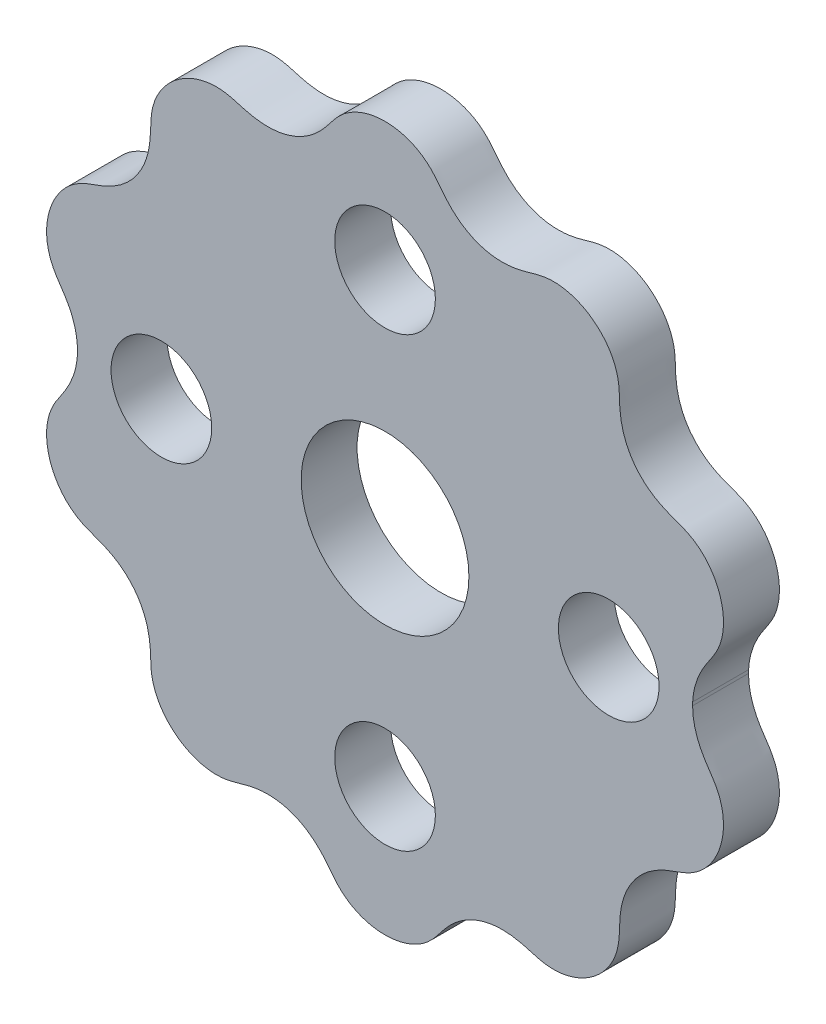
SolidWorks part; units mm, degrees
ref_plane "Front Plane" through (0, 0, 0) normal (0, 0, 1) x (1, 0, 0)
ref_plane "Top Plane" through (0, 0, 0) normal (0, 1, 0) x (1, 0, 0)
ref_plane "Right Plane" through (0, 0, 0) normal (1, 0, 0) x (0, 0, -1)
sketch "Sketch2" plane through (0, 0, 0) normal (0, 0, 1) x (1, 0, 0)
  spline S0 degree 4 poles (25.7736, 13.6742) (25.8686, 13.6396) (26.0587, 13.5707) (26.4395, 13.4348) (27.0042, 13.2114) (27.6294, 12.8737) (28.3868, 12.2959) (29.1238, 11.4849) (29.7675, 10.4058) (30.2051, 9.0603) (30.3194, 7.7572) (30.1819, 6.6864) (29.9333, 5.8919) (29.6914, 5.3551) (29.4615, 4.9441) (29.2046, 4.5499) (28.9379, 4.1623) (28.6806, 3.776) (28.4419, 3.3849) (28.2266, 2.9879) (28.0374, 2.5839) (27.8738, 2.1703) (27.7378, 1.7443) (27.6309, 1.3144) (27.5637, 0.9252) (27.5253, 0.6016) (27.5084, 0.3452) (27.502, 0.1683) (27.4994, 0.0141) (27.5004, -0.1164) (27.5075, -0.34) (27.5238, -0.57) (27.5481, -0.7918) (27.5805, -1.0166) (27.6209, -1.2405) (27.6691, -1.4621) (27.7251, -1.682) (27.7886, -1.9) (27.8772, -2.1695) (27.998, -2.4878) (28.159, -2.8512) (28.3712, -3.2608) (28.6095, -3.6641) (28.8695, -4.0622) (29.143, -4.4598) (29.4106, -4.8616) (29.6529, -5.2796) (29.9094, -5.8265) (30.1722, -6.6328) (30.3203, -7.7183) (30.2089, -9.0614) (29.7491, -10.4641) (29.0339, -11.6246) (28.2481, -12.4251) (27.5333, -12.9239) (26.9793, -13.2134) (26.518, -13.4062) (26.0478, -13.5746) (25.5777, -13.7437) (24.8251, -14.0429) (23.8272, -14.5611) (22.8619, -15.3341) (22.0408, -16.3838) (21.5281, -17.3765) (21.2286, -18.2328) (21.0669, -19.0171) (20.9945, -19.7066) (20.9671, -20.2928) (20.9548, -20.7736) (20.9338, -21.2542) (20.8816, -21.7329) (20.7645, -22.3233) (20.4996, -23.1258) (19.979, -24.0851) (19.0973, -25.1016) (17.8982, -25.9622) (16.6335, -26.4775) (15.3979, -26.6788) (14.3959, -26.6234) (13.6603, -26.4593) (12.9394, -26.2468) (12.0379, -25.9873) (10.7995, -25.7763) (9.4348, -25.8506) (8.155, -26.2277) (7.1615, -26.7369) (6.4222, -27.2569) (5.7489, -27.8783) (5.2229, -28.4924) (4.8001, -29.0515) (4.4288, -29.5161) (4.1076, -29.8677) (3.6695, -30.271) (2.9854, -30.7618) (1.9994, -31.2314) (0.6852, -31.5347) (-0.7982, -31.5227) (-2.1286, -31.1899) (-3.1354, -30.6771) (-3.8296, -30.1398) (-4.2741, -29.694) (-4.5985, -29.309) (-4.9048, -28.9102) (-5.2144, -28.5137) (-5.7398, -27.8898) (-6.5562, -27.1045) (-7.6045, -26.4371) (-8.8668, -25.9995) (-9.9704, -25.8363) (-10.8711, -25.8289) (-11.7772, -25.941) (-12.56, -26.1315) (-13.2279, -26.3354) (-13.7999, -26.4904) (-14.2652, -26.583) (-14.8548, -26.6479) (-15.6935, -26.6381) (-16.7623, -26.4344) (-18.0046, -25.9019) (-19.2024, -25.0089) (-20.0893, -23.9357) (-20.6017, -22.8989) (-20.838, -22.0286) (-20.9247, -21.3834) (-20.9528, -20.8637) (-20.9682, -20.2138) (-21.0163, -19.2751) (-21.2322, -18.0581) (-21.7483, -16.8235) (-22.5022, -15.7699) (-23.2898, -15.0102) (-24.0155, -14.4818) (-24.8142, -14.0462) (-25.5582, -13.7448) (-26.216, -13.5184) (-26.8773, -13.2642) (-27.5129, -12.9475) (-28.2929, -12.3942) (-29.1125, -11.514) (-29.7992, -10.3524) (-30.1827, -9.1076) (-30.2943, -7.9868) (-30.2217, -6.9667) (-30.0227, -6.0839) (-29.6912, -5.3029) (-29.2692, -4.6417) (-28.8241, -3.9982) (-28.3124, -3.2056) (-27.7762, -2.087) (-27.4747, -0.7693) (-27.4783, 0.5483) (-27.69, 1.6524) (-27.995, 2.5366) (-28.4131, 3.3667) (-28.9144, 4.1405) (-29.4478, 4.8854) (-29.8755, 5.6941) (-30.1894, 6.6884) (-30.3178, 7.8534) (-30.1867, 9.1453) (-29.73, 10.4906) (-29.0541, 11.5854) (-28.2608, 12.4161) (-27.4308, 13.0027) (-26.6298, 13.3794) (-25.7856, 13.6599) (-24.9483, 13.986) (-24.1413, 14.4028) (-23.3891, 14.9273) (-22.5742, 15.6842) (-21.7934, 16.7389) (-21.2546, 17.9804) (-21.0239, 19.207) (-20.9698, 20.1553) (-20.9543, 20.8132) (-20.9286, 21.3394) (-20.8458, 21.9932) (-20.6135, 22.8703) (-20.105, 23.9119) (-19.2235, 24.988) (-18.0363, 25.8823) (-16.8046, 26.4204) (-15.6294, 26.6538) (-14.5575, 26.6486) (-13.6299, 26.4657) (-12.7464, 26.1793) (-11.8556, 25.9573) (-10.9573, 25.8345) (-10.0623, 25.8304) (-8.9783, 25.9741) (-7.7449, 26.3752) (-6.5945, 27.0646) (-5.6973, 27.9205) (-5.1021, 28.652) (-4.6279, 29.2741) (-4.1293, 29.8791) (-3.3447, 30.5603) (-2.2037, 31.1655) (-0.8541, 31.5172) (0.6396, 31.5396) (1.9567, 31.2449) (3.0472, 30.7366) (3.8145, 30.165) (4.312, 29.6579) (4.758, 29.1071) (5.1767, 28.5513) (5.694, 27.9368) (6.5186, 27.158) (7.6239, 26.4287) (9.0591, 25.9) (10.618, 25.7735) (11.8417, 25.9449) (12.7488, 26.1895) (13.3714, 26.3756) (13.8742, 26.5092) (14.5145, 26.6257) (15.4149, 26.6693) (16.5588, 26.5019) (17.8531, 25.9896) (19.0722, 25.1259) (19.9624, 24.1085) (20.4861, 23.1543) (20.7542, 22.3592) (20.8743, 21.7781) (20.9297, 21.3067) (20.9588, 20.7145) (20.9715, 20.0161) (21.0326, 19.2124) (21.2066, 18.3158) (21.4928, 17.4614) (21.9899, 16.4625) (22.797, 15.3981) (23.756, 14.6083) (24.7551, 14.0754) (25.5107, 13.7689) (25.9833, 13.5971) (26.4571, 13.4291) (26.9231, 13.2393) (27.4841, 12.9541) (28.209, 12.4597) (29.0072, 11.6606) (29.7341, 10.498) (30.2035, 9.0908) (30.3103, 7.8665) (30.2094, 6.9015) (30.0311, 6.2024) (29.8725, 5.7531) (29.6737, 5.3199) (29.4381, 4.9059) (29.1762, 4.5083) (28.9064, 4.1163) (28.6476, 3.7244) (28.4087, 3.3272) (28.1943, 2.9233) (28.0069, 2.5131) (27.8663, 2.1443) (27.7637, 1.822) (27.6905, 1.55) (27.6395, 1.3305) (27.5962, 1.1088) (27.5608, 0.8861) (27.5332, 0.6665) (27.5135, 0.4371) (27.5017, 0.1876) (27.4989, 0.0253) (27.5024, -0.2192) (27.5166, -0.5014) (27.5498, -0.8265) (27.611, -1.2167) (27.7115, -1.6488) (27.8412, -2.077) (27.999, -2.4933) (28.1829, -2.9002) (28.3936, -3.3001) (28.6285, -3.694) (28.8834, -4.0824) (29.1501, -4.4703) (29.4108, -4.8625) (29.6474, -5.27) (29.8993, -5.8027) (30.1624, -6.5933) (30.3178, -7.6627) (30.2232, -8.9686) (29.8049, -10.3216) (29.1767, -11.4109) (28.4518, -12.234) (27.7035, -12.8248) (27.0836, -13.1737) (26.5212, -13.4046) (26.1404, -13.5414) (25.95, -13.6102) (25.8548, -13.6445) knots 0 0 0 0 0 0.001683 0.003365 0.00673 0.010096 0.013461 0.019157 0.024853 0.030833 0.036813 0.040728 0.042685 0.044642 0.046599 0.048557 0.050514 0.052471 0.054324 0.056177 0.05803 0.059883 0.061736 0.063589 0.065442 0.066368 0.067294 0.067726 0.068157 0.069102 0.070046 0.07099 0.071934 0.072878 0.073822 0.074766 0.07571 0.076654 0.077598 0.079487 0.081375 0.083263 0.085271 0.087279 0.089287 0.091295 0.093303 0.095311 0.099327 0.10536 0.111393 0.117532 0.123672 0.127828 0.129906 0.131984 0.134062 0.13614 0.138218 0.140297 0.14754 0.154783 0.158546 0.162308 0.166071 0.169834 0.171835 0.173836 0.175837 0.177838 0.179839 0.18184 0.185842 0.191853 0.197864 0.204025 0.210187 0.214358 0.218528 0.220613 0.222699 0.226869 0.234139 0.241409 0.245158 0.248907 0.252656 0.256405 0.260363 0.262342 0.264322 0.266301 0.26828 0.272239 0.278287 0.284335 0.290518 0.296702 0.300887 0.302979 0.305072 0.307165 0.309257 0.31135 0.313442 0.320738 0.328034 0.331771 0.335507 0.339243 0.34298 0.346923 0.348895 0.350866 0.352838 0.35481 0.358753 0.36478 0.370806 0.377097 0.383388 0.387716 0.38988 0.392044 0.394208 0.396372 0.4007 0.40768 0.41466 0.418384 0.422107 0.425831 0.429555 0.433483 0.435447 0.437411 0.44134 0.445268 0.451273 0.457277 0.46359 0.466747 0.469903 0.474246 0.478589 0.48076 0.482932 0.487275 0.49428 0.501285 0.505164 0.509043 0.512922 0.516801 0.520588 0.524375 0.528163 0.53195 0.537849 0.543748 0.549576 0.555403 0.55907 0.562736 0.566403 0.57007 0.573873 0.577676 0.581479 0.585283 0.592319 0.599356 0.603737 0.605928 0.608119 0.610309 0.6125 0.616881 0.623154 0.629427 0.635413 0.641398 0.645313 0.649228 0.653143 0.657058 0.66077 0.664483 0.668195 0.671908 0.67891 0.685912 0.690254 0.692424 0.694595 0.698936 0.703277 0.709588 0.715899 0.721906 0.727913 0.731842 0.735772 0.737737 0.739702 0.743632 0.747357 0.751083 0.758533 0.76551 0.772487 0.776814 0.778977 0.78114 0.783303 0.785466 0.789793 0.796081 0.80237 0.808398 0.814427 0.818372 0.820345 0.822317 0.82429 0.826263 0.830208 0.833945 0.837683 0.841421 0.845158 0.852451 0.859745 0.861836 0.863928 0.86602 0.868112 0.870203 0.872295 0.876479 0.88266 0.888841 0.894891 0.900942 0.902922 0.904902 0.906882 0.908862 0.910842 0.912822 0.914802 0.916782 0.918657 0.920532 0.922408 0.924283 0.92522 0.926158 0.927096 0.928033 0.928971 0.929909 0.930846 0.931784 0.932647 0.933575 0.934502 0.936356 0.938211 0.940065 0.94192 0.943774 0.945629 0.947484 0.949442 0.951401 0.95336 0.955319 0.957277 0.959236 0.963154 0.969139 0.975125 0.980826 0.986527 0.989895 0.993263 0.996632 0.998316 1 1 1 1 1 construction
  spline S1 degree 4 poles (27.5, 0) (27.5, -0.049) (27.5014, -0.146) (27.5075, -0.34) (27.5238, -0.57) (27.5481, -0.7918) (27.5805, -1.0166) (27.6209, -1.2405) (27.6691, -1.4621) (27.7251, -1.682) (27.7886, -1.9) (27.8772, -2.1695) (27.998, -2.4878) (28.159, -2.8512) (28.3712, -3.2608) (28.6095, -3.6641) (28.8695, -4.0622) (29.143, -4.4598) (29.4106, -4.8616) (29.6529, -5.2796) (29.9094, -5.8265) (30.1722, -6.6328) (30.3203, -7.7183) (30.2089, -9.0614) (29.7491, -10.4641) (29.0339, -11.6246) (28.2481, -12.4251) (27.5333, -12.9239) (26.9793, -13.2134) (26.518, -13.4062) (26.0478, -13.5746) (25.5777, -13.7437) (24.8251, -14.0429) (23.8272, -14.5611) (22.8619, -15.3341) (22.0408, -16.3838) (21.5281, -17.3765) (21.2286, -18.2328) (21.0669, -19.0171) (20.9945, -19.7066) (20.9671, -20.2928) (20.9548, -20.7736) (20.9338, -21.2542) (20.8816, -21.7329) (20.7645, -22.3233) (20.4996, -23.1258) (19.979, -24.0851) (19.0973, -25.1016) (17.8982, -25.9622) (16.6335, -26.4775) (15.3979, -26.6788) (14.3959, -26.6234) (13.6603, -26.4593) (12.9394, -26.2468) (12.0379, -25.9873) (10.7995, -25.7763) (9.4348, -25.8506) (8.155, -26.2277) (7.1615, -26.7369) (6.4222, -27.2569) (5.7489, -27.8783) (5.2229, -28.4924) (4.8001, -29.0515) (4.4288, -29.5161) (4.1076, -29.8677) (3.6695, -30.271) (2.9854, -30.7618) (1.9994, -31.2314) (0.6852, -31.5347) (-0.7982, -31.5227) (-2.1286, -31.1899) (-3.1354, -30.6771) (-3.8296, -30.1398) (-4.2741, -29.694) (-4.5985, -29.309) (-4.9048, -28.9102) (-5.2144, -28.5137) (-5.7398, -27.8898) (-6.5562, -27.1045) (-7.6045, -26.4371) (-8.8668, -25.9995) (-9.9704, -25.8363) (-10.8711, -25.8289) (-11.7772, -25.941) (-12.56, -26.1315) (-13.2279, -26.3354) (-13.7999, -26.4904) (-14.2652, -26.583) (-14.8548, -26.6479) (-15.6935, -26.6381) (-16.7623, -26.4344) (-18.0046, -25.9019) (-19.2024, -25.0089) (-20.0893, -23.9357) (-20.6017, -22.8989) (-20.838, -22.0286) (-20.9247, -21.3834) (-20.9528, -20.8637) (-20.9682, -20.2138) (-21.0163, -19.2751) (-21.2322, -18.0581) (-21.7483, -16.8235) (-22.5022, -15.7699) (-23.2898, -15.0102) (-24.0155, -14.4818) (-24.8142, -14.0462) (-25.5582, -13.7448) (-26.216, -13.5184) (-26.8773, -13.2642) (-27.5129, -12.9475) (-28.2929, -12.3942) (-29.1125, -11.514) (-29.7992, -10.3524) (-30.1827, -9.1076) (-30.2943, -7.9868) (-30.2217, -6.9667) (-30.0227, -6.0839) (-29.6912, -5.3029) (-29.2692, -4.6417) (-28.8241, -3.9982) (-28.3124, -3.2056) (-27.7762, -2.087) (-27.4747, -0.7693) (-27.4783, 0.5483) (-27.69, 1.6524) (-27.995, 2.5366) (-28.4131, 3.3667) (-28.9144, 4.1405) (-29.4478, 4.8854) (-29.8755, 5.6941) (-30.1894, 6.6884) (-30.3178, 7.8534) (-30.1867, 9.1453) (-29.73, 10.4906) (-29.0541, 11.5854) (-28.2608, 12.4161) (-27.4308, 13.0027) (-26.6298, 13.3794) (-25.7856, 13.6599) (-24.9483, 13.986) (-24.1413, 14.4028) (-23.3891, 14.9273) (-22.5742, 15.6842) (-21.7934, 16.7389) (-21.2546, 17.9804) (-21.0239, 19.207) (-20.9698, 20.1553) (-20.9543, 20.8132) (-20.9286, 21.3394) (-20.8458, 21.9932) (-20.6135, 22.8703) (-20.105, 23.9119) (-19.2235, 24.988) (-18.0363, 25.8823) (-16.8046, 26.4204) (-15.6294, 26.6538) (-14.5575, 26.6486) (-13.6299, 26.4657) (-12.7464, 26.1793) (-11.8556, 25.9573) (-10.9573, 25.8345) (-10.0623, 25.8304) (-8.9783, 25.9741) (-7.7449, 26.3752) (-6.5945, 27.0646) (-5.6973, 27.9205) (-5.1021, 28.652) (-4.6279, 29.2741) (-4.1293, 29.8791) (-3.3447, 30.5603) (-2.2037, 31.1655) (-0.8541, 31.5172) (0.6396, 31.5396) (1.9567, 31.2449) (3.0472, 30.7366) (3.8145, 30.165) (4.312, 29.6579) (4.758, 29.1071) (5.1767, 28.5513) (5.694, 27.9368) (6.5186, 27.158) (7.6239, 26.4287) (9.0591, 25.9) (10.618, 25.7735) (11.8417, 25.9449) (12.7488, 26.1895) (13.3714, 26.3756) (13.8742, 26.5092) (14.5145, 26.6257) (15.4149, 26.6693) (16.5588, 26.5019) (17.8531, 25.9896) (19.0722, 25.1259) (19.9624, 24.1085) (20.4861, 23.1543) (20.7542, 22.3592) (20.8743, 21.7781) (20.9297, 21.3067) (20.9588, 20.7145) (20.9715, 20.0161) (21.0326, 19.2124) (21.2066, 18.3158) (21.4928, 17.4614) (21.9899, 16.4625) (22.797, 15.3981) (23.756, 14.6083) (24.7551, 14.0754) (25.5107, 13.7689) (25.9833, 13.5971) (26.4571, 13.4291) (26.9231, 13.2393) (27.4841, 12.9541) (28.209, 12.4597) (29.0072, 11.6606) (29.7341, 10.498) (30.2035, 9.0908) (30.3103, 7.8665) (30.2094, 6.9015) (30.0311, 6.2024) (29.8725, 5.7531) (29.6737, 5.3199) (29.4381, 4.9059) (29.1762, 4.5083) (28.9064, 4.1163) (28.6476, 3.7244) (28.4087, 3.3272) (28.1943, 2.9233) (28.0069, 2.5131) (27.8663, 2.1443) (27.7637, 1.822) (27.6905, 1.55) (27.6395, 1.3305) (27.5962, 1.1088) (27.5608, 0.8861) (27.5332, 0.6665) (27.5135, 0.4371) (27.5045, 0.2462) (27.5016, 0.1492) (27.5008, 0.1006) knots 0.068157 0.068157 0.068157 0.068157 0.068157 0.069102 0.070046 0.07099 0.071934 0.072878 0.073822 0.074766 0.07571 0.076654 0.077598 0.079487 0.081375 0.083263 0.085271 0.087279 0.089287 0.091295 0.093303 0.095311 0.099327 0.10536 0.111393 0.117532 0.123672 0.127828 0.129906 0.131984 0.134062 0.13614 0.138218 0.140297 0.14754 0.154783 0.158546 0.162308 0.166071 0.169834 0.171835 0.173836 0.175837 0.177838 0.179839 0.18184 0.185842 0.191853 0.197864 0.204025 0.210187 0.214358 0.218528 0.220613 0.222699 0.226869 0.234139 0.241409 0.245158 0.248907 0.252656 0.256405 0.260363 0.262342 0.264322 0.266301 0.26828 0.272239 0.278287 0.284335 0.290518 0.296702 0.300887 0.302979 0.305072 0.307165 0.309257 0.31135 0.313442 0.320738 0.328034 0.331771 0.335507 0.339243 0.34298 0.346923 0.348895 0.350866 0.352838 0.35481 0.358753 0.36478 0.370806 0.377097 0.383388 0.387716 0.38988 0.392044 0.394208 0.396372 0.4007 0.40768 0.41466 0.418384 0.422107 0.425831 0.429555 0.433483 0.435447 0.437411 0.44134 0.445268 0.451273 0.457277 0.46359 0.466747 0.469903 0.474246 0.478589 0.48076 0.482932 0.487275 0.49428 0.501285 0.505164 0.509043 0.512922 0.516801 0.520588 0.524375 0.528163 0.53195 0.537849 0.543748 0.549576 0.555403 0.55907 0.562736 0.566403 0.57007 0.573873 0.577676 0.581479 0.585283 0.592319 0.599356 0.603737 0.605928 0.608119 0.610309 0.6125 0.616881 0.623154 0.629427 0.635413 0.641398 0.645313 0.649228 0.653143 0.657058 0.66077 0.664483 0.668195 0.671908 0.67891 0.685912 0.690254 0.692424 0.694595 0.698936 0.703277 0.709588 0.715899 0.721906 0.727913 0.731842 0.735772 0.737737 0.739702 0.743632 0.747357 0.751083 0.758533 0.76551 0.772487 0.776814 0.778977 0.78114 0.783303 0.785466 0.789793 0.796081 0.80237 0.808398 0.814427 0.818372 0.820345 0.822317 0.82429 0.826263 0.830208 0.833945 0.837683 0.841421 0.845158 0.852451 0.859745 0.861836 0.863928 0.86602 0.868112 0.870203 0.872295 0.876479 0.88266 0.888841 0.894891 0.900942 0.902922 0.904902 0.906882 0.908862 0.910842 0.912822 0.914802 0.916782 0.918657 0.920532 0.922408 0.924283 0.92522 0.926158 0.927096 0.928033 0.928971 0.929909 0.930846 0.931784 0.931784 0.931784 0.931784 0.931784
  spline S2 degree 2 poles (27.5, 0) (27.4999, 0.1496) (27.5075, 0.2991) knots 0 0 0 1 1 1
extrude "Boss-Extrude1" add sketch "Sketch2" along normal blind 5 contours S1 S2
sketch "Sketch3" plane through (0, 0, 5) normal (0, 0, 1) x (1, 0, 0)
  line L0 (0, 0) -> (0, 27.7917) construction
  line L1 (0, 0) -> (22.0436, 4.7953) construction
  circle A0 centre (0, 0) radius 7.5
  dimension "D1" = 77.727
extrude "Cut-Extrude1" cut sketch "Sketch3" against normal blind 5
sketch "Sketch4" plane through (0, 0, 5) normal (0, 0, 1) x (1, 0, 0)
  line L0 (0, 0) -> (0, 25.4722) construction
  line L1 (0, 0) -> (41.12, 0) construction
  circle A0 centre (0, 0) radius 20
  circle A1 centre (20, 0) radius 4.5
  circle A2 centre (0, -20) radius 4.5
  circle A3 centre (-20, 0) radius 4.5
  circle A4 centre (0, 20) radius 4.5
  point P16 (0, 0)
  dimension "D2" = 4
  dimension "D1" = 90
extrude "Cut-Extrude2" cut sketch "Sketch4" against normal blind 5 contours A0 A4 | A0 A4 | A0 A3 | A0 A3 | A0 A2 | A0 A2 | A0 A1 | A0 A1
